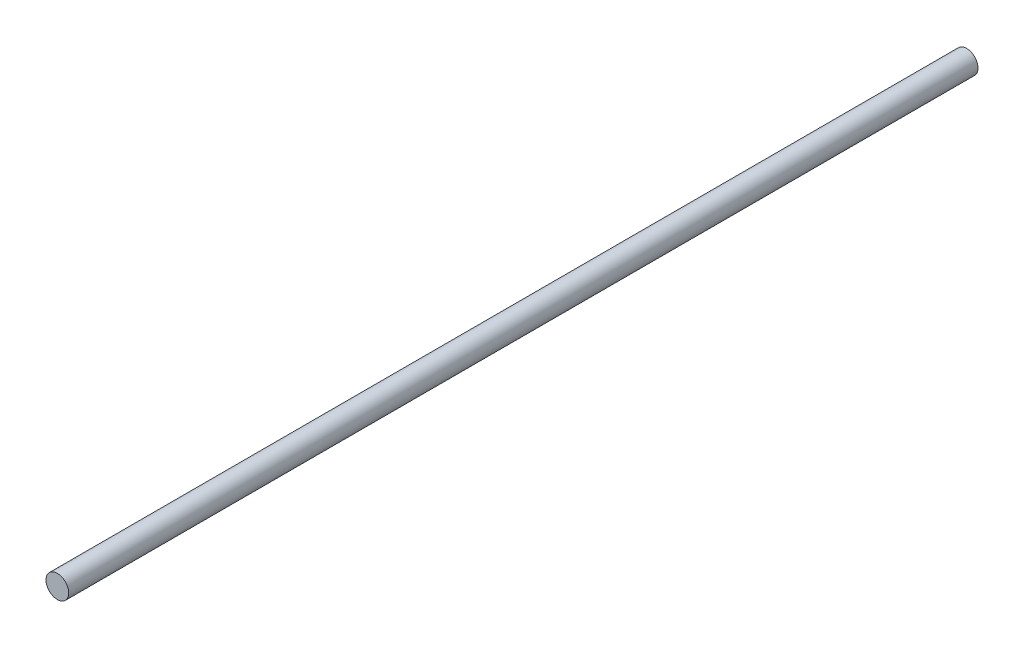
SolidWorks part; units mm, degrees
ref_plane "Front Plane" through (0, 0, 0) normal (0, 0, 1) x (1, 0, 0)
ref_plane "Top Plane" through (0, 0, 0) normal (0, 1, 0) x (1, 0, 0)
ref_plane "Right Plane" through (0, 0, 0) normal (1, 0, 0) x (0, 0, -1)
sketch "Sketch1" plane through (0, 0, 0) normal (0, 0, 1) x (1, 0, 0)
  circle A0 centre (0, 0) radius 7.5
  dimension "D1" = 15
extrude "Boss-Extrude1" add sketch "Sketch1" along normal blind 600 contours A0
